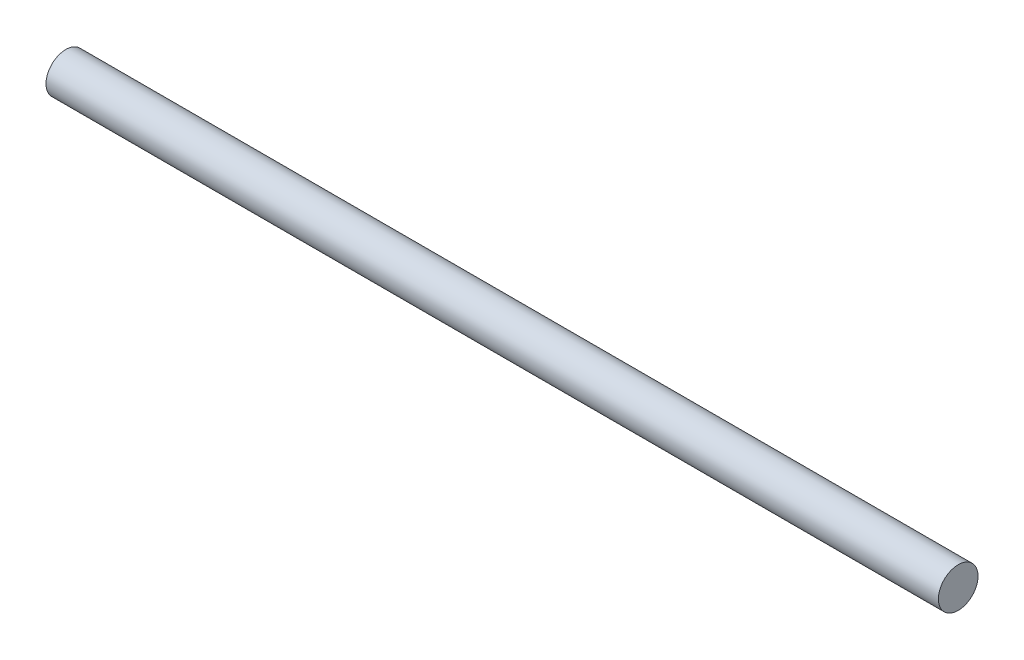
SolidWorks part; units mm, degrees
ref_plane "Front Plane" through (0, 0, 0) normal (0, 0, 1) x (1, 0, 0)
ref_plane "Top Plane" through (0, 0, 0) normal (0, 1, 0) x (1, 0, 0)
ref_plane "Right Plane" through (0, 0, 0) normal (1, 0, 0) x (0, 0, -1)
sketch "Sketch1" plane through (0, 0, 0) normal (1, 0, 0) x (0, 0, -1)
  circle A0 centre (0, 0) radius 1
extrude "Boss-Extrude1" add sketch "Sketch1" along normal blind 45
